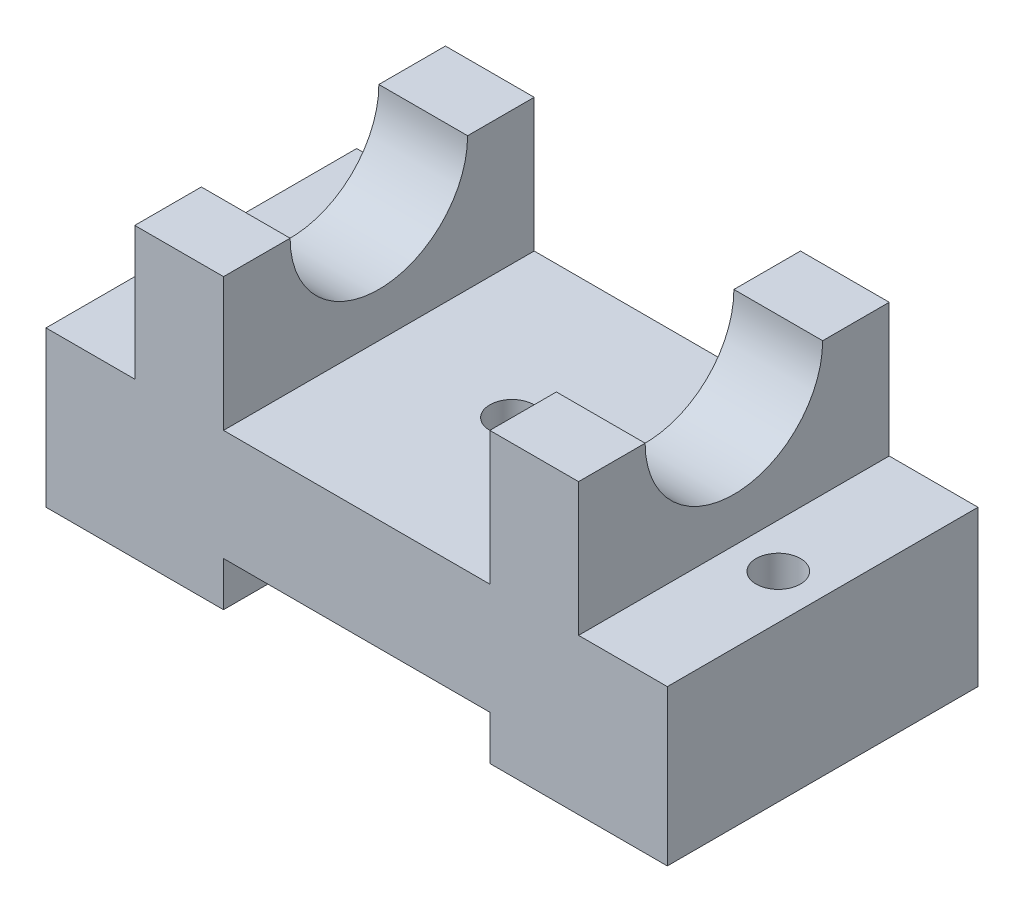
SolidWorks part; units mm, degrees
ref_plane "Front Plane" through (0, 0, 0) normal (0, 0, 1) x (1, 0, 0)
ref_plane "Top Plane" through (0, 0, 0) normal (0, 1, 0) x (1, 0, 0)
ref_plane "Right Plane" through (0, 0, 0) normal (1, 0, 0) x (0, 0, -1)
sketch "Sketch2" plane through (0, 0, 0) normal (0, 0, 1) x (1, 0, 0)
  line L0 (0, 0) -> (40, 0)
  line L1 (140, 0) -> (140, 35)
  line L2 (140, 35) -> (120, 35)
  line L3 (120, 35) -> (120, 65)
  line L4 (120, 65) -> (100, 65)
  line L5 (100, 65) -> (100, 35)
  line L6 (100, 35) -> (40, 35)
  line L7 (40, 35) -> (40, 65)
  line L8 (40, 65) -> (20, 65)
  line L9 (20, 65) -> (20, 35)
  line L10 (20, 35) -> (0, 35)
  line L11 (0, 35) -> (0, 0)
  line L12 (40, 0) -> (40, 10)
  line L13 (40, 10) -> (100, 10)
  line L14 (100, 10) -> (100, 0)
  line L15 (100, 0) -> (140, 0)
  dimension "D1" = 140
  dimension "D2" = 35
  dimension "D3" = 20
  dimension "D4" = 30
  dimension "D5" = 60
  dimension "D6" = 20
  dimension "D7" = 10
extrude "Boss-Extrude1" add sketch "Sketch2" against normal blind 70
sketch "Sketch3" plane through (120, 0, 0) normal (1, 0, 0) x (0, 0, -1)
  line L0 (70, 65) -> (0, 65) construction
  arc A0 (15, 65) -> (55, 65) centre (35, 65) ccw
  dimension "D1" = 20
extrude "Cut-Extrude1" cut sketch "Sketch3" against normal through all and the other way through all
sketch "Sketch4" plane through (0, 35, 0) normal (0, 1, 0) x (1, 0, 0)
  line L0 (0, 35) -> (140, 35) construction
  line L1 (0, 70) -> (0, 0) construction
  line L2 (140, 70) -> (140, 0) construction
  line L3 (130, 70) -> (130, 0) construction
  line L4 (100, 70) -> (40, 70) construction
  line L5 (70, 70) -> (70, 0) construction
  line L6 (100, 0) -> (40, 0) construction
  line L7 (140, 70) -> (120, 70) construction
  line L8 (140, 0) -> (120, 0) construction
  line L9 (10, 70) -> (10, 0) construction
  line L10 (20, 70) -> (0, 70) construction
  line L11 (20, 0) -> (0, 0) construction
  circle A0 centre (130, 35) radius 5
  circle A1 centre (10, 35) radius 5
  circle A2 centre (70, 35) radius 5
  dimension "D1" = 10
  dimension "D2" = 10
  dimension "D3" = 10
extrude "Cut-Extrude3" cut sketch "Sketch4" against normal through all
